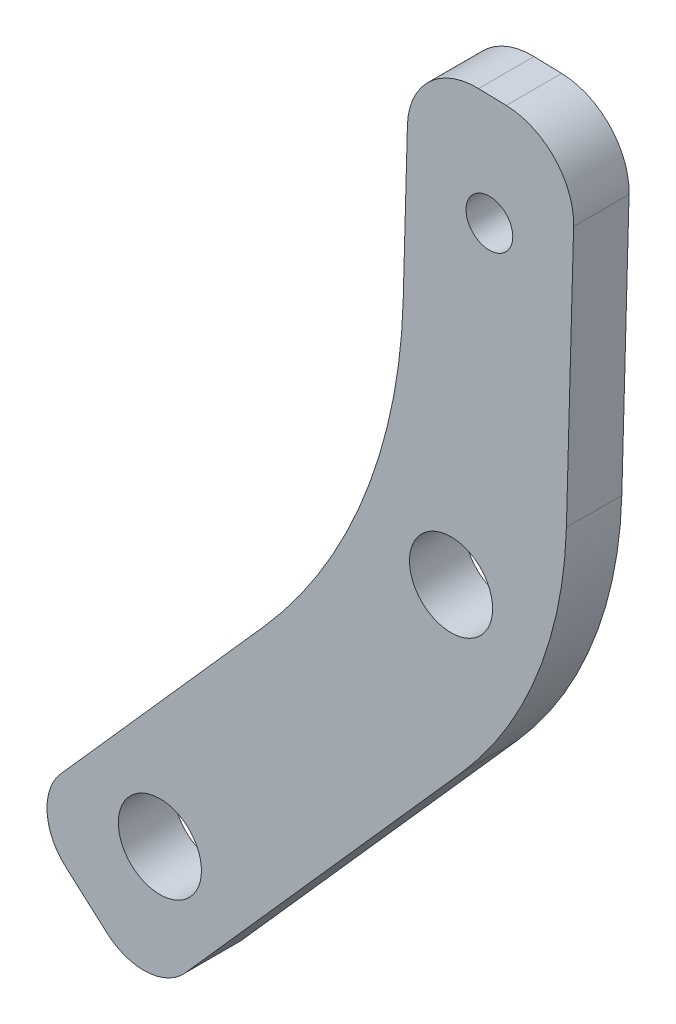
SolidWorks part; units mm, degrees
ref_plane "Front" through (0, 0, 0) normal (0, 0, 1) x (1, 0, 0)
ref_plane "Top" through (0, 0, 0) normal (0, 1, 0) x (1, 0, 0)
ref_plane "Right" through (0, 0, 0) normal (1, 0, 0) x (0, 0, -1)
sketch "Sketch1" plane through (0, 0, 0) normal (0, 0, 1) x (1, 0, 0)
  line L0 (7.9038, 3.731) -> (-21.9544, -29.9362)
  line L1 (8.862, 38.7179) -> (-3.1335, 39.0464)
  line L2 (-3.1335, 39.0464) -> (-3.9721, 8.4255)
  line L3 (-3.9721, 8.4255) -> (-30.9323, -21.974)
  line L4 (2.8642, 38.8822) -> (2.3284, 19.3174) construction
  line L5 (-21.9544, -29.9362) -> (-30.9323, -21.974)
  line L7 (7.9038, 3.731) -> (8.862, 38.7179)
  circle A0 centre (-21.1352, -19.9698) radius 3
  circle A1 centre (2.6452, 30.8852) radius 1.6883
  dimension "D3" = 6
  dimension "D4" = 8
  dimension "D5" = 12
  dimension "D7" = 90
  dimension "D6" = 8
  dimension "D2" = 12
  dimension "D9" = 35
  dimension "D10" = 140
extrude "Boss-Extrude1" add sketch "Sketch1" along normal blind 4
fillet "Fillet1" radius 4 2 edges at (-30.9323, -21.974, 2) (-21.9544, -29.9362, 2)
fillet "Fillet4" radius 30 1 edges at (7.9038, 3.731, 2)
fillet "Fillet5" radius 40 1 edges at (-3.9721, 8.4255, 2)
fillet "Fillet6" radius 5 2 edges at (8.862, 38.7179, 2) (-3.1335, 39.0464, 2)
sketch "Sketch6" plane through (0, 0, 4) normal (0, 0, 1) x (1, 0, 0)
  line L0 (6.1133, 4.4388) -> (-6.3594, 9.3692) construction
  arc A0 (0.6588, -4.4382) -> (8.2028, 14.6461) centre (-21.786, 15.4673) ccw construction
  arc A1 (-13.6321, -2.4668) -> (-3.5735, 22.9789) centre (-43.5586, 24.0739) ccw construction
  circle A2 centre (-0.1231, 6.904) radius 3
  dimension "D1" = 6
extrude "Cut-Extrude2" cut sketch "Sketch6" against normal blind 34
